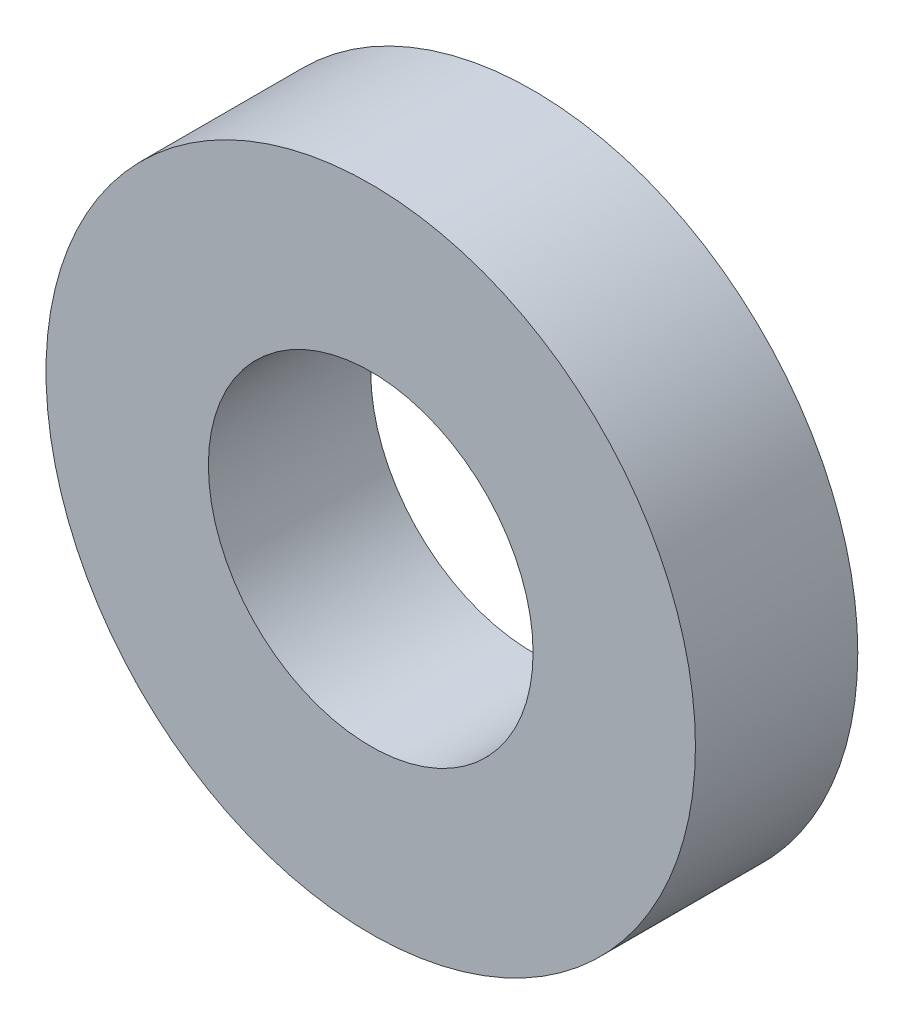
SolidWorks part; units mm, degrees
ref_plane "Front Plane" through (0, 0, 0) normal (0, 0, 1) x (1, 0, 0)
ref_plane "Top Plane" through (0, 0, 0) normal (0, 1, 0) x (1, 0, 0)
ref_plane "Right Plane" through (0, 0, 0) normal (1, 0, 0) x (0, 0, -1)
sketch "Sketch1" plane through (0, 0, 0) normal (0, 0, 1) x (1, 0, 0)
  circle A0 centre (0, 0) radius 3
  circle A1 centre (0, 0) radius 6
  dimension "D1" = 6
  dimension "D2" = 12
extrude "Boss-Extrude1" add sketch "Sketch1" along normal blind 3
